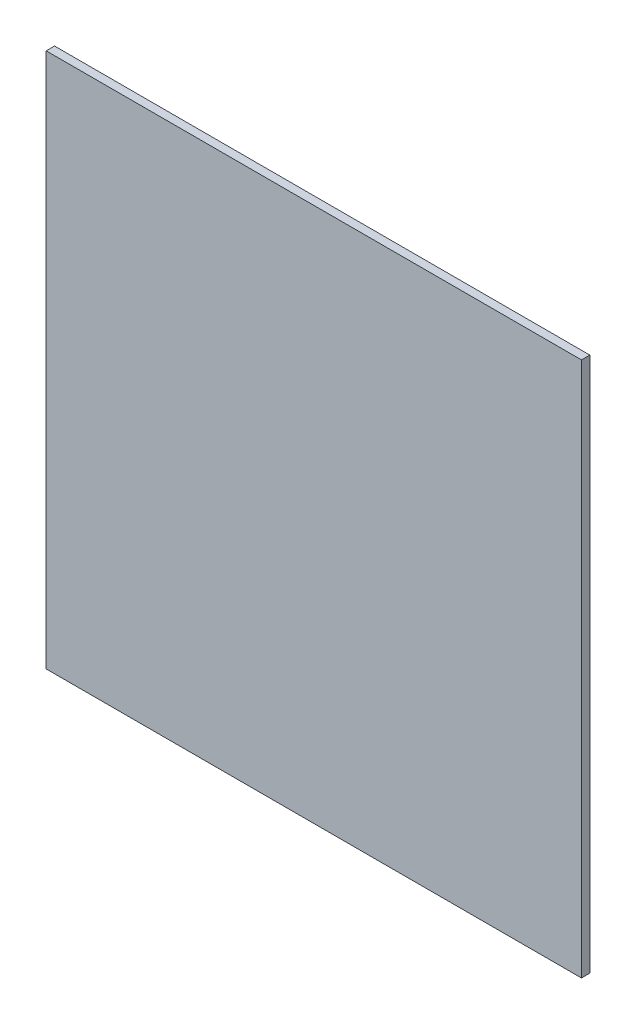
SolidWorks part; units mm, degrees
ref_plane "Front Plane" through (0, 0, 0) normal (0, 0, 1) x (1, 0, 0)
ref_plane "Top Plane" through (0, 0, 0) normal (0, 1, 0) x (1, 0, 0)
ref_plane "Right Plane" through (0, 0, 0) normal (1, 0, 0) x (0, 0, -1)
sketch "Sketch2" plane through (0, 0, 0) normal (0, 0, 1) x (1, 0, 0)
  circle A0 centre (0, 0) radius 533.4
  circle A1 centre (0, 0) radius 584.2
  dimension "D1" = 1168.4
  dimension "D2" = 1066.8
extrude "Boss-Extrude1" add sketch "Sketch2" along normal blind 19.05
sketch "Sketch3" plane through (0, 0, 19.05) normal (0, 0, 1) x (1, 0, 0)
  line L1 (609.6, 609.6) -> (-609.6, 609.6)
  line L2 (609.6, 609.6) -> (609.6, -609.6)
  line L3 (609.6, -609.6) -> (-609.6, -609.6)
  line L4 (-609.6, 609.6) -> (-609.6, -609.6)
  line L5 (609.6, 609.6) -> (-609.6, -609.6) construction
  line L6 (609.6, -609.6) -> (-609.6, 609.6) construction
  point P0 (0, 0)
  dimension "D1" = 1219.2
  dimension "D2" = 1219.2
extrude "Stock" add sketch "Sketch3" against normal blind 19.05 separate body
sketch "Sketch4" plane through (0, 0, 19.05) normal (0, 0, 1) x (1, 0, 0)
  line L1 (609.6, -609.6) -> (482.6, -609.6)
  line L2 (609.6, -609.6) -> (609.6, -482.6)
  line L3 (609.6, -482.6) -> (482.6, -482.6)
  line L4 (482.6, -609.6) -> (482.6, -482.6)
  dimension "D1" = 127
  dimension "D2" = 127
